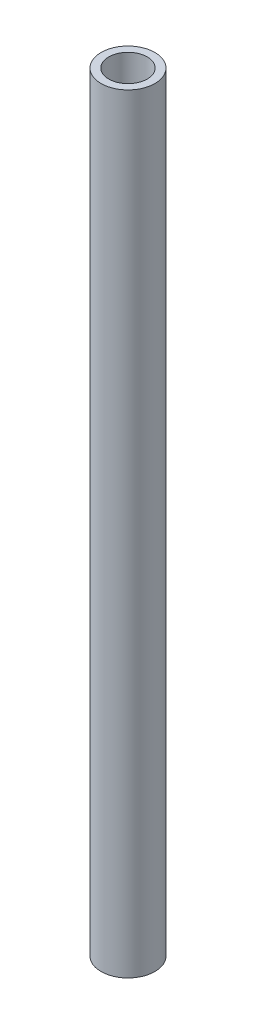
SolidWorks part; units mm, degrees
ref_plane "Front Plane" through (0, 0, 0) normal (0, 0, 1) x (1, 0, 0)
ref_plane "Top Plane" through (0, 0, 0) normal (0, 1, 0) x (1, 0, 0)
ref_plane "Right Plane" through (0, 0, 0) normal (1, 0, 0) x (0, 0, -1)
sketch "Sketch1" plane through (0, 0, 0) normal (0, 1, 0) x (1, 0, 0)
  circle A0 centre (0, 0) radius 2.5
  circle A1 centre (0, 0) radius 3.5
  dimension "D1" = 5
  dimension "D2" = 7
extrude "Boss-Extrude1" add sketch "Sketch1" along normal blind 100
